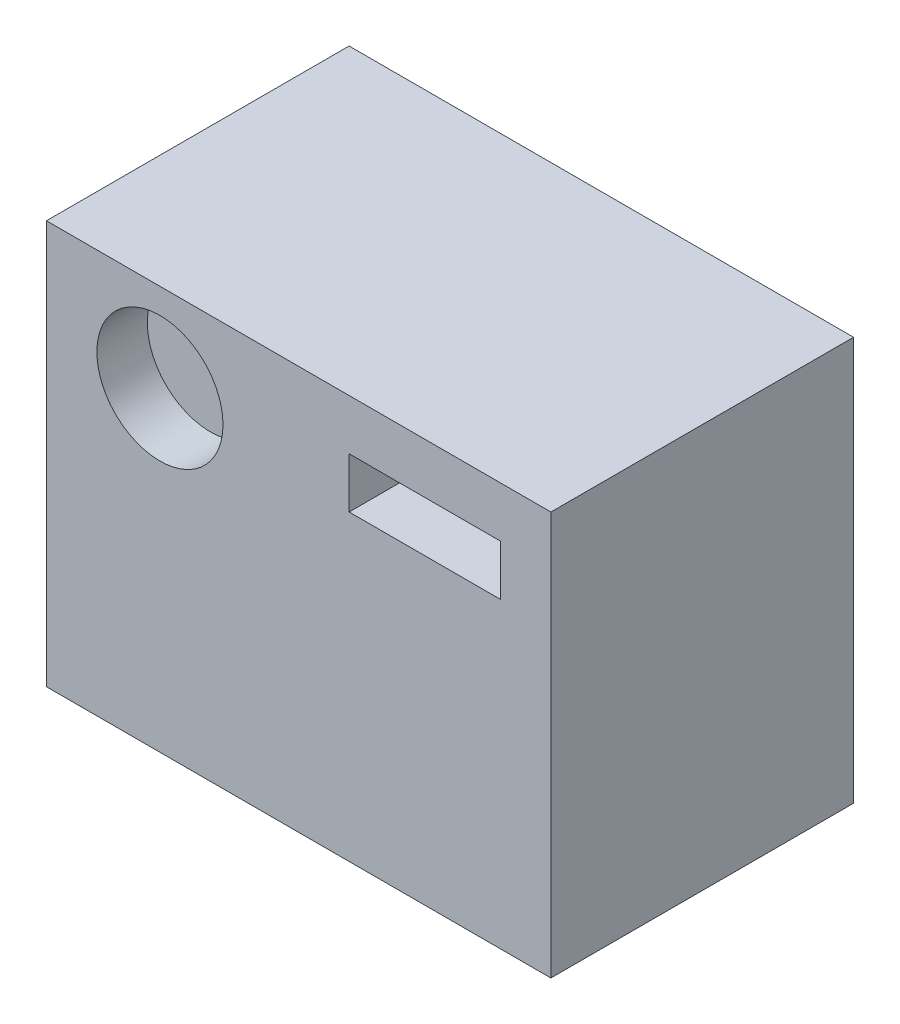
SolidWorks part; units mm, degrees
ref_plane "Alzado" through (0, 0, 0) normal (0, 0, 1) x (1, 0, 0)
ref_plane "Planta" through (0, 0, 0) normal (0, 1, 0) x (1, 0, 0)
ref_plane "Vista lateral" through (0, 0, 0) normal (1, 0, 0) x (0, 0, -1)
sketch "Croquis1" plane through (0, 0, 0) normal (0, 0, 1) x (1, 0, 0)
  line L1 (0, 0) -> (20, 0)
  line L2 (0, 0) -> (0, 16)
  line L3 (0, 16) -> (20, 16)
  line L4 (20, 0) -> (20, 16)
  dimension "D1" = 20
  dimension "D2" = 16
extrude "Saliente-Extruir1" add sketch "Croquis1" along normal blind 12
sketch "Croquis2" plane through (0, 0, 12) normal (0, 0, 1) x (1, 0, 0)
  line L0 (20, 16) -> (0, 16) construction
  line L1 (12, 14) -> (18, 14)
  line L2 (12, 14) -> (12, 12)
  line L3 (12, 12) -> (18, 12)
  line L4 (18, 14) -> (18, 12)
  line L5 (0, 16) -> (0, 0) construction
  line L6 (20, 0) -> (20, 16) construction
  circle A0 centre (4.5, 12.5) radius 2.5
  dimension "D3" = 5
  dimension "D1" = 6
  dimension "D2" = 2
  dimension "D4" = 3.5
  dimension "D5" = 4.5
  dimension "D6" = 2
  dimension "D7" = 2
extrude "Cortar-Extruir1" cut sketch "Croquis2" against normal blind 2
